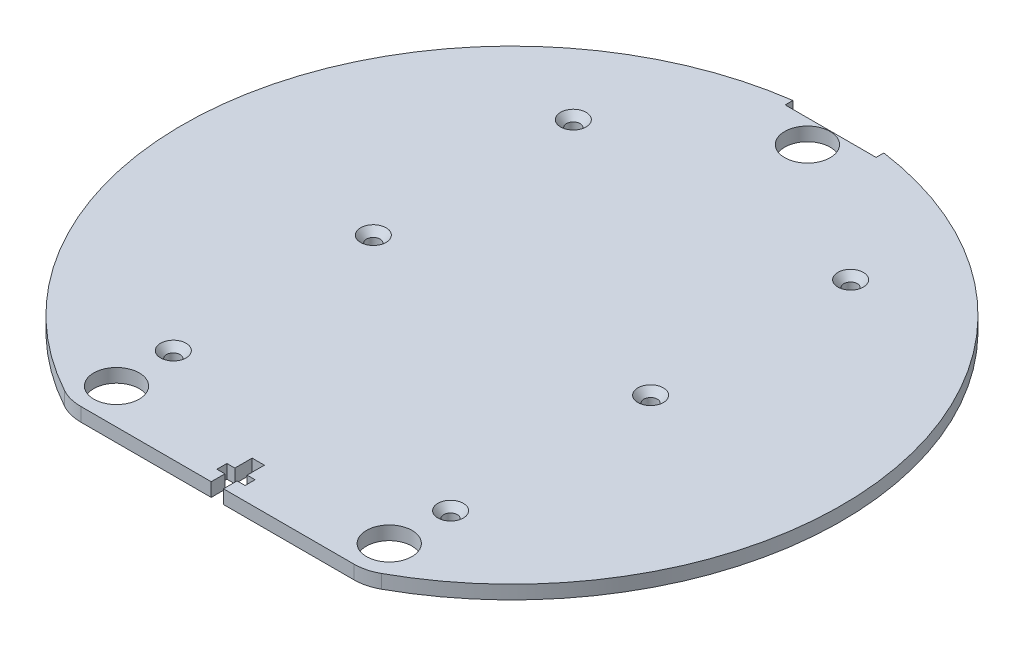
SolidWorks part; units mm, degrees
material "ABS"
ref_plane "Front Plane" through (0, 0, 0) normal (0, 0, 1) x (1, 0, 0)
ref_plane "Top Plane" through (0, 0, 0) normal (0, 1, 0) x (1, 0, 0)
ref_plane "Right Plane" through (0, 0, 0) normal (1, 0, 0) x (0, 0, -1)
sketch "Sketch1" plane through (0, 0, 0) normal (0, 1, 0) x (1, 0, 0)
  line L0 (0, -85) -> (0, 0) construction
  line L1 (30.03, -64.8129) -> (-30.03, -64.8129)
  arc A0 (34.8348, -63.5829) -> (-34.8348, -63.5829) centre (0, 0) ccw
  circle A1 centre (0, -85) radius 38.25 construction
  arc A2 (30.03, -64.8129) -> (34.8348, -63.5829) centre (30.03, -54.8129) ccw
  arc A3 (-30.03, -64.8129) -> (-34.8348, -63.5829) centre (-30.03, -54.8129) cw
  point P12 (-32.4891, -64.8129)
  dimension "D1" = 145
  dimension "D3" = 76.5
  dimension "D4" = 10
  dimension "D2" = 85
extrude "Boss-Extrude1" add sketch "Sketch1" along normal blind 3
sketch "Sketch2" plane through (0, 3, 0) normal (0, 1, 0) x (1, 0, 0)
  line L1 (-30.5, -44) -> (30.5, -44) construction
  line L2 (-30.5, -44) -> (-30.5, 44) construction
  line L3 (-30.5, 44) -> (30.5, 44) construction
  line L4 (30.5, -44) -> (30.5, 44) construction
  line L5 (-30.5, -44) -> (30.5, 44) construction
  line L6 (-30.5, 44) -> (30.5, -44) construction
  circle A0 centre (-30.5, 44) radius 1.5
  circle A1 centre (30.5, 44) radius 1.5
  circle A2 centre (30.5, 0) radius 1.5
  circle A3 centre (30.5, -44) radius 1.5
  circle A4 centre (-30.5, -44) radius 1.5
  circle A5 centre (-30.5, 0) radius 1.5
  point P0 (0, 0)
  dimension "D3" = 3
  dimension "D1" = 61
  dimension "D2" = 88
extrude "Cut-Extrude1" cut sketch "Sketch2" against normal through all
chamfer "Chamfer1" distance 1.5 angle 41 6 edges at (30.5, 3, -42.5) (30.5, 3, 1.5) (30.5, 3, 45.5) (-30.5, 3, 45.5) (-30.5, 3, 1.5) (-30.5, 3, -42.5)
sketch "Sketch3" plane through (0, 3, 0) normal (0, 1, 0) x (1, 0, 0)
  line L0 (-30.03, -64.8129) -> (30.03, -64.8129) construction
  line L1 (1.35, -61.8129) -> (3.1, -61.8129)
  line L2 (-3.1, -59.6129) -> (-1.35, -59.6129)
  line L3 (-3.1, -59.6129) -> (-3.1, -61.8129)
  line L4 (-3.1, -61.8129) -> (-1.35, -61.8129)
  line L5 (3.1, -59.6129) -> (3.1, -61.8129)
  line L6 (-1.35, -64.8129) -> (1.35, -64.8129)
  line L7 (-1.35, -64.8129) -> (-1.35, -61.8129)
  line L8 (1.35, -59.6129) -> (3.1, -59.6129)
  line L9 (1.35, -64.8129) -> (1.35, -61.8129)
  line L11 (-1.35, -59.6129) -> (-1.35, -55.8129)
  line L12 (-1.35, -55.8129) -> (1.35, -55.8129)
  line L13 (1.35, -59.6129) -> (1.35, -55.8129)
  point P10 (0, -64.8129)
  point P14 (0, -64.8129)
  dimension "D1" = 2.7
  dimension "D2" = 6.2
  dimension "D3" = 2.2
  dimension "D4" = 3
  dimension "D5" = 9
extrude "Cut-Extrude2" cut sketch "Sketch3" against normal through all
sketch "Sketch4" plane through (0, 3, 0) normal (0, 1, 0) x (1, 0, 0)
  line L1 (-10, 71.807) -> (10, 71.807)
  line L2 (-10, 71.807) -> (-10, 70.107)
  line L3 (-10, 70.107) -> (10, 70.107)
  line L4 (10, 71.807) -> (10, 70.107)
  arc A0 (34.8348, -63.5829) -> (-34.8348, -63.5829) centre (0, 0) ccw construction
  dimension "D1" = 1.7
  dimension "D2" = 20
extrude "Cut-Extrude3" cut sketch "Sketch4" against normal through all
sketch "Sketch5" plane through (0, 3, 0) normal (0, 1, 0) x (1, 0, 0)
  line L0 (0, 0) -> (0, 65) construction
  circle A0 centre (0, 65) radius 5
  circle A1 centre (30, -57) radius 5
  circle A2 centre (-30, -57) radius 5
  dimension "D1" = 10
  dimension "D2" = 65
  dimension "D3" = 57
  dimension "D4" = 30
extrude "Cut-Extrude4" cut sketch "Sketch5" against normal through all
equation "\"smallPulleyTeeth\"= 30"
equation "\"largePulleyTeeth\"= 30"
equation "\"eighthThick\"= 3.0mm"
equation "\"sixteenthThick\"= 1.7mm"
equation "\"quarterThick\"=6.0mm"
equation "\"OD\"= 145mm"
equation "\"puckAngle\"= 60.5deg"
equation "\"puckDiam\"= 76.5mm"
equation "\"puckDist\"= 85mm"
equation "\"scoopFillet\"= 5mm"
equation "\"axlePress\"= 5.9mm"
equation "\"press\"= 0.2mm"
equation "\"wheelClear\"= 0.3mm"
equation "\"10-32clear\"= 4.8mm"
equation "\"10-32tap\"= 4.45mm"
equation "\"6-32clear\"= 3.3mm"
equation "\"8-32clear\"= 4.0mm"
equation "\"4-40clear\"= 3.0mm"
equation "\"wheelHeight\"= 22mm"
equation "\"wheelWell\"= 65mm"
equation "\"ledSmall\"= 3.1mm"
equation "\"ledLarge\"= 4.2mm"
equation "\"ledLength\"= 4.2mm"
equation "\"D1@Sketch1\"=\"OD\""
equation "\"D1@Boss-Extrude1\"=\"eighthThick\""
equation "\"D3@Sketch2\"=\"4-40clear\""
equation "\"D3@Sketch1\"=\"puckDiam\""
equation "\"D2@Sketch1\"=\"puckDist\""
equation "\"4-40close\"= 2.7mm"
equation "\"4-40nutThick\"= 2.2mm"
equation "\"4-40nutWidth\"= 6.2mm"
equation "\"D1@Sketch4\"=\"sixteenthThick\""
equation "\"D1@Sketch3\"=\"4-40close\""
equation "\"4-40insertHeight\"= 3.5mm"
equation "\"4-40insert\"= 4mm"
equation "\"D2@Sketch3\"=\"4-40nutWidth\""
equation "\"D3@Sketch3\"=\"4-40nutThick\""
